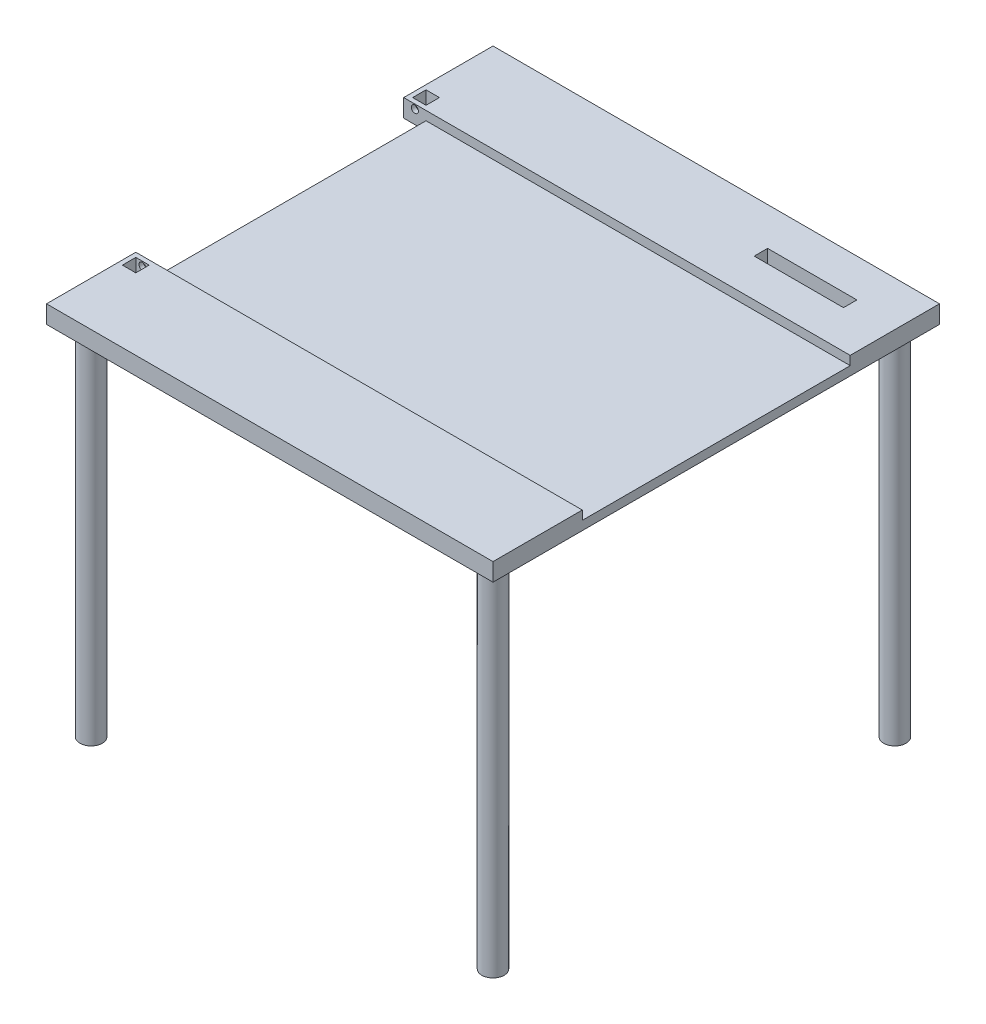
SolidWorks part; units mm, degrees
ref_plane "Front Plane" through (0, 0, 0) normal (0, 0, 1) x (1, 0, 0)
ref_plane "Top Plane" through (0, 0, 0) normal (0, 1, 0) x (1, 0, 0)
ref_plane "Right Plane" through (0, 0, 0) normal (1, 0, 0) x (0, 0, -1)
sketch "Sketch1" plane through (0, 0, 0) normal (0, 1, 0) x (1, 0, 0)
  line L0 (0, 0) -> (1000, 0)
  line L1 (1000, 0) -> (1000, -1000)
  line L2 (1000, -1000) -> (0, -1000)
  line L3 (0, -1000) -> (0, 0)
extrude "Boss-Extrude1" add sketch "Sketch1" along normal blind 40
sketch "Sketch2" plane through (0, 40, 0) normal (0, 1, 0) x (1, 0, 0)
  line L1 (0, 0) -> (0, -1000) construction
  line L2 (0, -800) -> (1000, -800)
  line L3 (1000, -1000) -> (1000, 0) construction
  line L4 (1000, -800) -> (1000, -200)
  line L5 (1000, -200) -> (0, -200)
  line L6 (0, -200) -> (0, -800)
extrude "Cut-Extrude1" cut sketch "Sketch2" against normal blind 20
sketch "Sketch6" plane through (0, 0, 0) normal (0, -1, 0) x (-1, 0, 0)
  line L0 (0, -1000) -> (-50, -1000)
  line L7 (0, -1000) -> (-1000, -1000) construction
  line L9 (-50, -1000) -> (-50, -950)
  line L11 (-50, -950) -> (-950, -950)
  line L12 (-950, -950) -> (-950, -50)
  line L13 (-950, -50) -> (-50, -50)
  line L14 (-50, -50) -> (-50, -950)
  circle A0 centre (-50, -950) radius 25
  circle A1 centre (-950, -950) radius 25
  circle A2 centre (-950, -50) radius 25
  circle A3 centre (-50, -50) radius 25
extrude "Boss-Extrude8" add sketch "Sketch6" along normal blind 800 contours A0 | A1 | A2 | A3
sketch "Sketch7" plane through (0, 40, 0) normal (0, 1, 0) x (1, 0, 0)
  line L0 (0, -800) -> (10, -800)
  line L2 (0, -800) -> (1000, -800) construction
  line L3 (10, -800) -> (10, -840)
  line L4 (10, -150) -> (10, -190)
  line L5 (10, -190) -> (40, -190)
  line L6 (40, -190) -> (40, -160)
  line L7 (40, -160) -> (10, -160)
  line L8 (10, -840) -> (40, -840)
  line L9 (40, -840) -> (40, -810)
  line L10 (40, -810) -> (10, -810)
extrude "Cut-Extrude3" cut sketch "Sketch7" against normal blind 50 contours L6 L7 L4 L5 | L9 L10 L3 L8
sketch "Sketch8" plane through (0, 0, 200) normal (0, 0, 1) x (1, 0, 0)
  line L0 (0, 40) -> (25, 40)
  line L1 (0, 40) -> (1000, 40) construction
  line L2 (25, 40) -> (25, 30)
  circle A0 centre (25, 30) radius 8
extrude "Cut-Extrude4" cut sketch "Sketch8" against normal blind 30
sketch "Sketch9" plane through (0, 0, 800) normal (0, 0, -1) x (-1, 0, 0)
  line L0 (0, 40) -> (-25, 40)
  line L1 (-1000, 40) -> (0, 40) construction
  line L2 (-25, 40) -> (-25, 30)
  circle A0 centre (-25, 30) radius 8
extrude "Cut-Extrude5" cut sketch "Sketch9" against normal blind 30
sketch "Sketch10" plane through (0, 20, 0) normal (0, 1, 0) x (1, 0, 0)
  line L0 (0, -200) -> (50, -200)
  line L1 (1000, -200) -> (0, -200) construction
  line L2 (50, -200) -> (50, -800)
  line L3 (0, -800) -> (1000, -800) construction
  line L4 (50, -800) -> (0, -800)
  line L5 (0, -800) -> (0, -200)
extrude "Cut-Extrude6" cut sketch "Sketch10" against normal blind 30
sketch "Sketch11" plane through (0, 40, 0) normal (0, 1, 0) x (1, 0, 0)
  line L0 (1000, -100) -> (900, -100)
  line L1 (1000, -200) -> (1000, 0) construction
  line L5 (700, -115) -> (900, -115)
  line L6 (900, -115) -> (900, -100)
  line L7 (900, -100) -> (800, -100)
  line L8 (900, -100) -> (900, -85)
  line L9 (900, -85) -> (700, -85)
  line L10 (700, -115) -> (700, -85)
extrude "Cut-Extrude7" cut sketch "Sketch11" against normal blind 30
